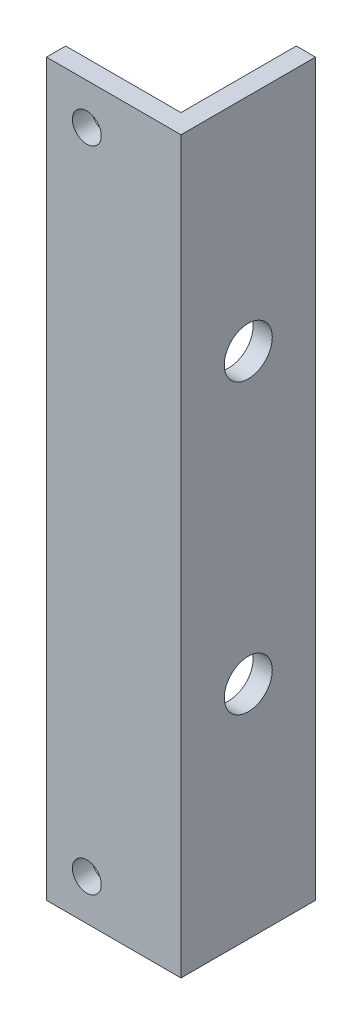
SolidWorks part; units mm, degrees
ref_plane "前视基准面" through (0, 0, 0) normal (0, 0, 1) x (1, 0, 0)
ref_plane "上视基准面" through (0, 0, 0) normal (0, 1, 0) x (1, 0, 0)
ref_plane "右视基准面" through (0, 0, 0) normal (1, 0, 0) x (0, 0, -1)
sketch "草图1" plane through (0, 0, 0) normal (0, 1, 0) x (1, 0, 0)
  line L0 (0, 0) -> (14, 0)
  line L1 (14, 0) -> (14, 14)
  line L2 (14, 14) -> (12, 14)
  line L3 (12, 14) -> (12, 2)
  line L4 (12, 2) -> (0, 2)
  line L5 (0, 2) -> (0, 0)
extrude "凸台-拉伸1" add sketch "草图1" along normal blind 76
sketch "草图2" plane through (0, 0, 0) normal (0, 0, 1) x (1, 0, 0)
  line L0 (0, 76) -> (0, 0) construction
  line L1 (0, 0) -> (14, 0) construction
  line L2 (0, 76) -> (14, 76) construction
  circle A0 centre (4.2, 4.25) radius 1.5
  circle A1 centre (4.2, 71.75) radius 1.5
  point P6 (0, 0)
  point P8 (4.8359, 2.0148)
  dimension "D1" = 4.2
  dimension "D5" = 3
  dimension "D6" = 3
  dimension "D2" = 4.25
  dimension "D3" = 4.2
  dimension "D4" = 4.25
extrude "切除-拉伸1" cut sketch "草图2" against normal blind 76
sketch "草图3" plane through (14, 0, 0) normal (1, 0, 0) x (0, 0, -1)
  line L0 (0, 76) -> (0, 0) construction
  circle A0 centre (7, 23) radius 2.5
  circle A1 centre (7, 53) radius 2.5
  point P6 (0, 38)
  dimension "D1" = 30
  dimension "D5" = 5
  dimension "D6" = 5
  dimension "D2" = 15
  dimension "D3" = 7
  dimension "D4" = 7
extrude "切除-拉伸2" cut sketch "草图3" against normal blind 76
